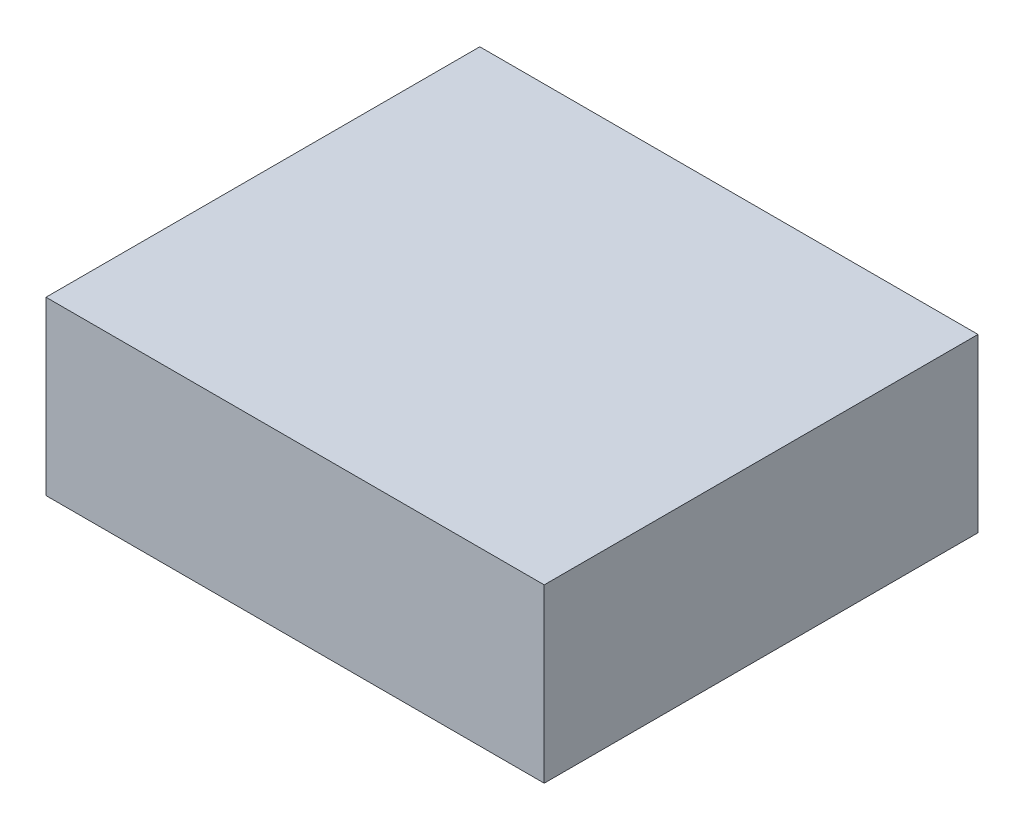
SolidWorks part; units mm, degrees
ref_plane "Front Plane" through (0, 0, 0) normal (0, 0, 1) x (1, 0, 0)
ref_plane "Top Plane" through (0, 0, 0) normal (0, 1, 0) x (1, 0, 0)
ref_plane "Right Plane" through (0, 0, 0) normal (1, 0, 0) x (0, 0, -1)
sketch "Sketch1" plane through (0, 0, 0) normal (0, 1, 0) x (1, 0, 0)
  line L1 (-5.8, 5.05) -> (5.8, 5.05)
  line L2 (-5.8, 5.05) -> (-5.8, -5.05)
  line L3 (-5.8, -5.05) -> (5.8, -5.05)
  line L4 (5.8, 5.05) -> (5.8, -5.05)
  line L5 (-5.8, 5.05) -> (5.8, -5.05) construction
  line L6 (-5.8, -5.05) -> (5.8, 5.05) construction
  point P0 (0, 0)
  dimension "D1" = 11.6
  dimension "D2" = 10.1
extrude "Boss-Extrude1" add sketch "Sketch1" along normal blind 4
sketch "Sketch2" plane through (0, 0, 0) normal (0, -1, 0) x (1, 0, 0)
  line L0 (0, 0) -> (-4.3, 0) construction
  line L1 (0, 0) -> (4.3, 0) construction
  line L2 (5.8, 5.05) -> (5.8, -5.05) construction
  line L3 (-5.8, 1.25) -> (-2.8, 1.25)
  line L4 (-5.8, 1.25) -> (-5.8, -1.25)
  line L5 (-5.8, -1.25) -> (-2.8, -1.25)
  line L6 (-2.8, 1.25) -> (-2.8, -1.25)
  line L7 (-5.8, 1.25) -> (-2.8, -1.25) construction
  line L8 (-5.8, -1.25) -> (-2.8, 1.25) construction
  line L9 (2.8, 1.25) -> (5.8, 1.25)
  line L10 (2.8, 1.25) -> (2.8, -1.25)
  line L11 (2.8, -1.25) -> (5.8, -1.25)
  line L12 (5.8, 1.25) -> (5.8, -1.25)
  line L13 (2.8, 1.25) -> (5.8, -1.25) construction
  line L14 (2.8, -1.25) -> (5.8, 1.25) construction
  dimension "D1" = 3
  dimension "D2" = 2.5
extrude "Boss-Extrude2" add sketch "Sketch2" along normal blind 0.0001
